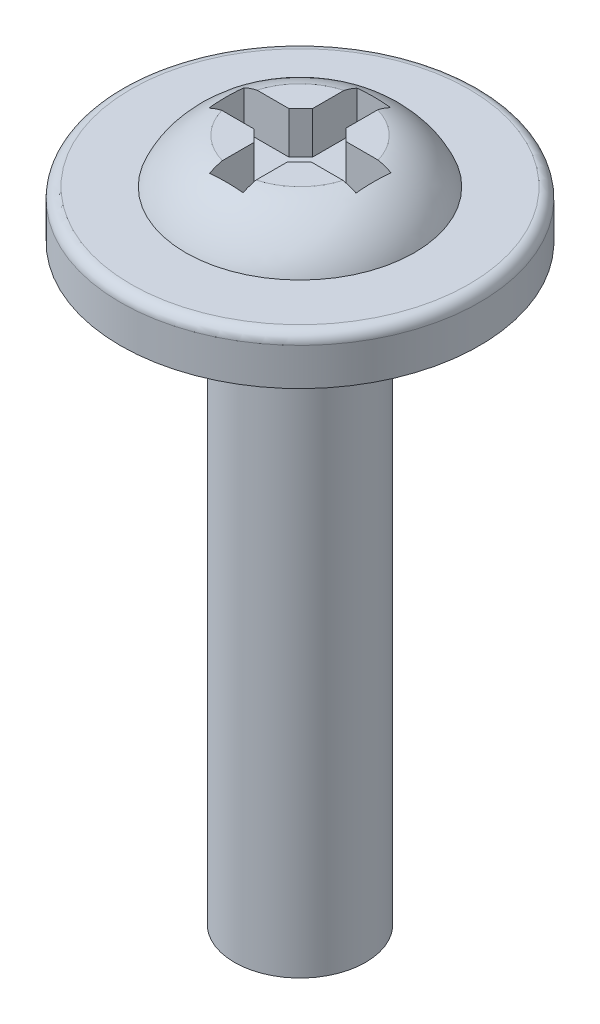
SolidWorks part; units mm, degrees
ref_plane "Front Plane" through (0, 0, 0) normal (0, 0, 1) x (1, 0, 0)
ref_plane "Top Plane" through (0, 0, 0) normal (0, 1, 0) x (1, 0, 0)
ref_plane "Right Plane" through (0, 0, 0) normal (1, 0, 0) x (0, 0, -1)
sketch "Sketch2" plane through (0, 0, 0) normal (1, 0, 0) x (0, 0, -1)
  line L0 (0, 12.7) -> (5.4229, 12.7)
  line L1 (0, 15.494) -> (0, 12.7)
  line L2 (0, 14.1478) -> (3.4544, 14.1478)
  line L3 (0, 15.494) -> (1.905, 15.494)
  line L4 (5.4229, 12.7) -> (5.4229, 14.1478)
  line L5 (3.4544, 14.1478) -> (5.4229, 14.1478)
  line L6 (0, 0) -> (1.9812, 0)
  line L7 (1.9812, 0) -> (1.9812, 12.7)
  line L8 (0, 0) -> (0, 25.8053) construction
  line L9 (0, 0) -> (0, -6.35)
  line L10 (0, 12.7) -> (0, 0)
  line L11 (1.9812, 0) -> (1.9812, -5.1526)
  line L12 (1.9812, -5.1526) -> (0, -6.35)
  spline S0 degree 3 poles (1.905, 15.494) (2.4859, 15.3632) (3.1698, 14.8318) (3.4544, 14.1478) knots 0 0 0 0 1 1 1 1
  dimension "D7" = 1.9812
  dimension "D1" = 5.4229
  dimension "D2" = 3.4544
  dimension "D3" = 1.4478
  dimension "D4" = 1.905
  dimension "D5" = 2.794
  dimension "D6" = 12.7
  dimension "D8" = 19.05
revolve "Revolve2" add sketch "Sketch2" angle 360 about L8
sketch "Sketch4" plane through (0, 15.494, 0) normal (0, 1, 0) x (1, 0, 0)
  line L0 (-0.508, 2.2288) -> (0.508, 2.2288)
  line L1 (-0.508, 2.2288) -> (-0.508, 0.8846)
  line L2 (-0.508, -2.2288) -> (0.508, -2.2288)
  line L3 (0.508, -2.2288) -> (0.508, -0.8846)
  line L4 (-2.2236, 0.5306) -> (-2.2236, -0.5306)
  line L5 (-2.2236, 0.5306) -> (-0.862, 0.5306)
  line L6 (2.2236, 0.5306) -> (2.2236, -0.5306)
  line L7 (2.2236, -0.5306) -> (0.862, -0.5306)
  line L8 (0.508, 0.8846) -> (0.862, 0.5306)
  line L9 (0.862, -0.5306) -> (0.508, -0.8846)
  line L10 (-0.508, -0.8846) -> (-0.862, -0.5306)
  line L11 (-0.862, 0.5306) -> (-0.508, 0.8846)
  line L12 (-0.508, -0.8846) -> (-0.508, -2.2288)
  line L13 (0.862, 0.5306) -> (2.2236, 0.5306)
  line L14 (0.508, 0.8846) -> (0.508, 2.2288)
  line L15 (-0.862, -0.5306) -> (-2.2236, -0.5306)
  circle A0 centre (0, 0) radius 2.286
  dimension "D1" = 4.572
  dimension "D2" = 1.016
extrude "Cut-Extrude1" cut sketch "Sketch4" against normal blind 1.27
fillet "Fillet1" radius 0.3175 1 edges at (0, 14.1478, -5.4229)
